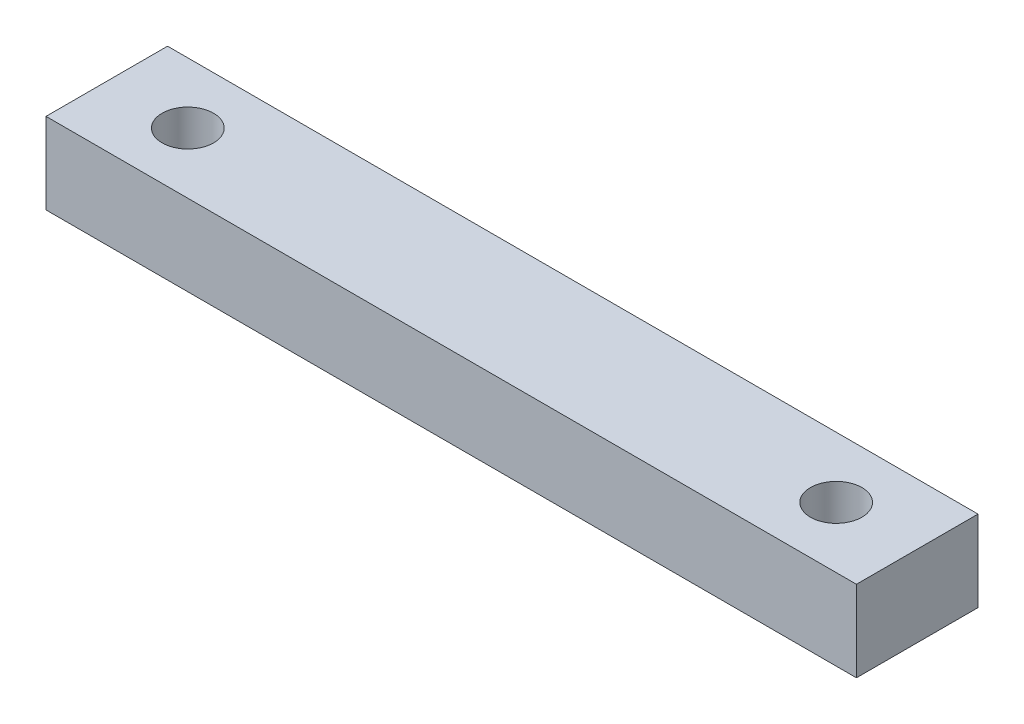
SolidWorks part; units mm, degrees
ref_plane "Front Plane" through (0, 0, 0) normal (0, 0, 1) x (1, 0, 0)
ref_plane "Top Plane" through (0, 0, 0) normal (0, 1, 0) x (1, 0, 0)
ref_plane "Right Plane" through (0, 0, 0) normal (1, 0, 0) x (0, 0, -1)
sketch "Sketch1" plane through (0, 0, 0) normal (0, 1, 0) x (1, 0, 0)
  line L0 (0, 7.5) -> (100, 7.5) construction
  line L1 (0, 0) -> (100, 0)
  line L2 (0, 0) -> (0, 15)
  line L3 (0, 15) -> (100, 15)
  line L4 (100, 0) -> (100, 15)
  line L5 (50, 15) -> (50, 0) construction
  circle A0 centre (10, 7.5) radius 3.175
  circle A1 centre (90, 7.5) radius 3.175
  point P11 (0, 0)
  dimension "D3" = 6.35
  dimension "D1" = 100
  dimension "D2" = 15
  dimension "D4" = 10
extrude "Boss-Extrude1" add sketch "Sketch1" along normal blind 10
